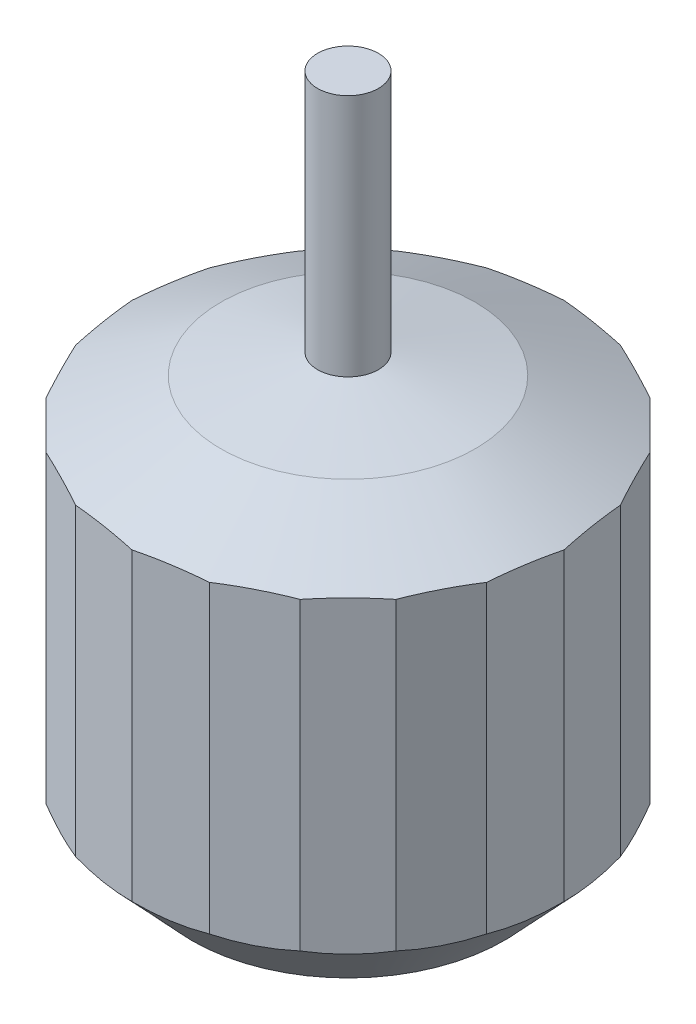
SolidWorks part; units mm, degrees
ref_plane "Front Plane" through (0, 0, 0) normal (0, 0, 1) x (1, 0, 0)
ref_plane "Top Plane" through (0, 0, 0) normal (0, 1, 0) x (1, 0, 0)
ref_plane "Right Plane" through (0, 0, 0) normal (1, 0, 0) x (0, 0, -1)
sketch "Sketch1" plane through (0, 0, 0) normal (0, 0, 1) x (1, 0, 0)
  line L0 (0, 0) -> (6.7496, 2.7958)
  line L1 (0, 63.4658) -> (2.54, 63.4658)
  line L2 (0, 63.4658) -> (0, 0)
  line L3 (6.7496, 2.7958) -> (13.0282, 7.1386)
  line L4 (18.0253, 37.8706) -> (18.0253, 12.468)
  line L5 (2.54, 63.4658) -> (2.54, 43.1458)
  line L6 (13.0282, 7.1386) -> (18.0253, 12.468)
  line L8 (0, 0) -> (10.3572, 4.2901) construction
  line L9 (18.0253, 12.468) -> (10.3572, 4.2901) construction
  line L11 (18.0253, 37.8706) -> (10.6051, 41.4548)
  line L12 (10.6051, 41.4548) -> (2.54, 43.1458)
  point P1 (13.0282, 7.1386)
  point P3 (6.7496, 2.7958)
  point P9 (0, 0)
  point P12 (0, 0)
  point P14 (0, 0)
  point P15 (0, 0)
  point P16 (0, 0)
  point P17 (0, 0)
  point P18 (0, 0)
  point P19 (6.652, 3.0208)
  point P20 (0, 0)
  point P21 (0, 0)
  point P22 (0, 0)
  dimension "D1" = 20.32
  dimension "D2" = 7.3057
  dimension "D3" = 7.3057
revolve "Revolve2" add sketch "Sketch1" angle 360 about L2
sketch "Sketch2" plane through (0, 63.4658, 0) normal (0, 1, 0) x (1, 0, 0)
  line L2 (-10.595, 14.5828) -> (-14.5828, 10.595)
  line L3 (-14.5828, 10.595) -> (-17.1431, 5.5701)
  line L4 (-17.1431, 5.5701) -> (-18.0253, 0)
  line L5 (-18.0253, 0) -> (-17.1431, -5.5701)
  line L6 (-17.1431, -5.5701) -> (-14.5828, -10.595)
  line L7 (-14.5828, -10.595) -> (-10.595, -14.5828)
  line L8 (-10.595, -14.5828) -> (-5.5701, -17.1431)
  line L9 (-5.5701, -17.1431) -> (0, -18.0253)
  line L10 (0, -18.0253) -> (5.5701, -17.1431)
  line L11 (5.5701, -17.1431) -> (10.595, -14.5828)
  line L12 (10.595, -14.5828) -> (14.5828, -10.595)
  line L13 (14.5828, -10.595) -> (17.1431, -5.5701)
  line L14 (17.1431, -5.5701) -> (18.0253, 0)
  line L15 (18.0253, 0) -> (17.1431, 5.5701)
  line L16 (17.1431, 5.5701) -> (14.5828, 10.595)
  line L17 (14.5828, 10.595) -> (10.595, 14.5828)
  line L18 (10.595, 14.5828) -> (5.5701, 17.1431)
  line L19 (5.5701, 17.1431) -> (0, 18.0253)
  line L20 (0, 18.0253) -> (-5.5701, 17.1431)
  line L21 (-5.5701, 17.1431) -> (-10.595, 14.5828)
  circle A0 centre (0, 0) radius 17.8034 construction
  circle A1 centre (0, 0) radius 18.0253 construction
  point P0 (0, 0)
  point P4 (-10.6598, 0)
extrude "Cut-Extrude2" cut sketch "Sketch2" against normal through all flip side to cut
sketch "Sketch3" plane through (0, 0, 0) normal (0, 0, 1) x (1, 0, 0)
  line L0 (5.1786, 2.145) -> (5.1786, -7.38)
  line L1 (0, 0) -> (10.3572, 4.2901) construction
  line L2 (5.1786, -7.38) -> (20, -25.0434)
  line L3 (0, 2.145) -> (-5.1786, 2.145) construction
  line L4 (20, -25.0434) -> (0, -25.0434)
  line L5 (-10.3572, 4.2901) -> (0, 0) construction
  line L8 (0, 2.145) -> (5.1786, 2.145)
  line L10 (0, 2.145) -> (0, -25.0434)
  dimension "D1" = 20
  dimension "D2" = 50
  dimension "D4" = 9.525
revolve "Revolve4" [suppressed] add sketch "Sketch3" angle 360 about L10
